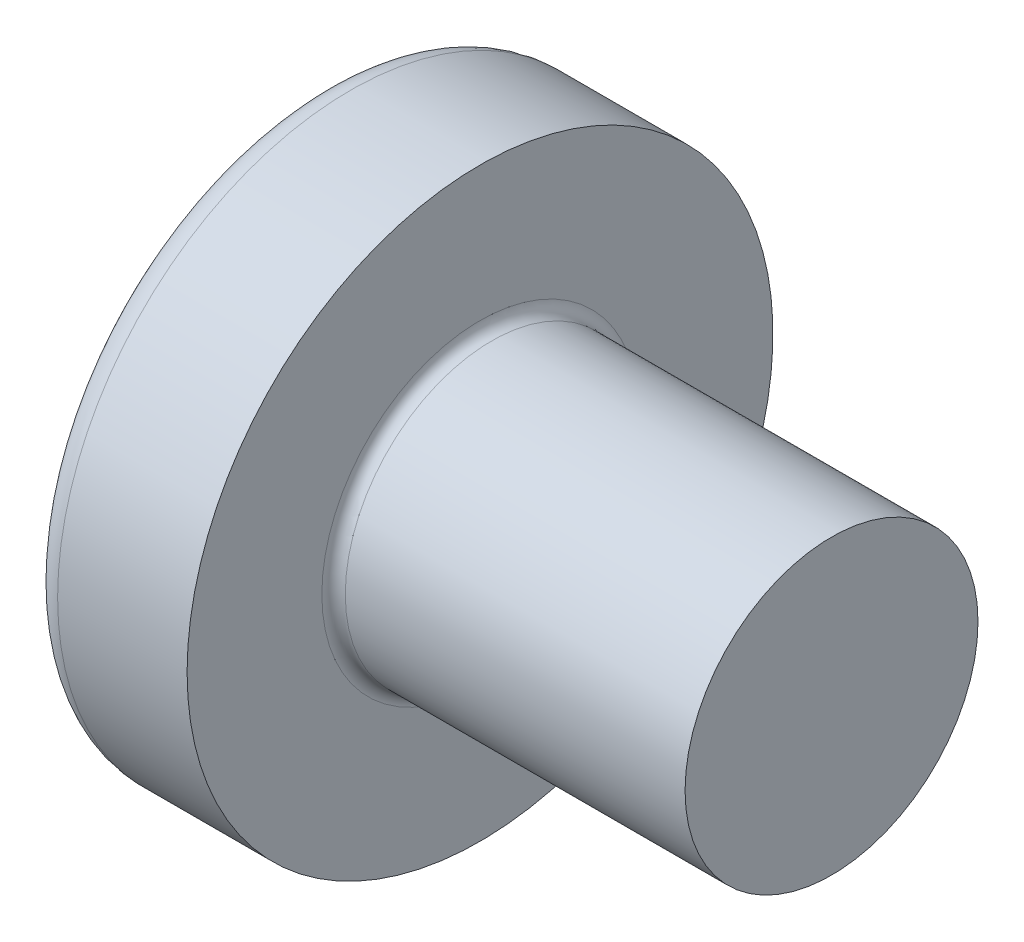
SolidWorks part; units mm, degrees
ref_plane "Plane1" through (0, 0, 0) normal (0, 0, 1) x (1, 0, 0)
ref_plane "Plane2" through (0, 0, 0) normal (0, 1, 0) x (1, 0, 0)
ref_plane "Plane3" through (0, 0, 0) normal (1, 0, 0) x (0, 0, -1)
sketch "BodySke" plane through (0, 0, 0) normal (0, 0, 1) x (1, 0, 0)
  line L0 (2.1, 1.25) -> (2.1, 2.5)
  line L1 (2.325, 6.35) -> (2.325, -3.175) construction
  line L2 (-25.4, 0) -> (127, 0) construction
  line L3 (5.1, 0) -> (0, 0)
  line L4 (2.1, 1.25) -> (5.1, 1.25)
  line L5 (5.1, 1.25) -> (5.1, 0)
  line L6 (0.995, 2.5) -> (2.1, 2.5)
  line L8 (2.1, 6.35) -> (2.1, -3.175) construction
  arc A0 (0.8032, 2.4043) -> (0, 0) centre (4, 0) ccw
  arc A2 (0.8032, 2.4043) -> (0.995, 2.5) centre (0.995, 2.26) cw
  dimension "Head_crown_rad" = 4
  dimension "Head_fillet_rad" = 0.24
  dimension "Length" = 3
  dimension "Head_ht" = 2.1
  dimension "Head_dia" = 5
  dimension "Advance" = 0.45
  dimension "Thread_nom" = 3
  dimension "Diameter" = 2.5
revolve "Base-Revolve" add sketch "BodySke"
cosmetic thread "ThreadCosmetic" [suppressed]
fillet "Fillet1" radius 0.1 1 edges at (2.1, 0, 1.25)
sketch "Sketch3" plane through (0, 0, 0) normal (1, 0, 0) x (0, 0, -1)
  line L0 (0.37, -1.3) -> (-0.37, -1.3)
  line L1 (0.37, -1.3) -> (0.37, 1.3)
  line L2 (-0.37, 1.3) -> (0.37, 1.3)
  line L3 (-0.37, 1.3) -> (-0.37, -1.3)
  dimension "Cross_dia" = 2.6
  dimension "D1" = 1.3
  dimension "Cross_width" = 0.74
  dimension "D2" = 0.37
ref_plane "Plane4" through (1.5, 0, 0) normal (1, 0, 0) x (0, 0, -1)
sketch "Sketch4" plane through (1.5, 0, 0) normal (1, 0, 0) x (0, 0, -1)
  line L0 (0.37, -0.5521) -> (-0.37, -0.5521)
  line L1 (0.37, -0.5521) -> (0.37, 0.5521)
  line L2 (-0.37, 0.5521) -> (0.37, 0.5521)
  line L3 (-0.37, 0.5521) -> (-0.37, -0.5521)
  dimension "D1" = 0.74
  dimension "D2" = 1.1043
  dimension "D3" = 0.37
  dimension "D4" = 0.5521
loft "Recess" cut profiles "Sketch3", "Sketch4"
pattern_circular "RecPat" count 2 every 90 about axis through (0, 0, 0) along (1, 0, 0) of "Recess"
sketch "RecCorSke" plane through (0, 0, 0) normal (0, 0, 1) x (1, 0, 0)
  line L0 (-3.175, 0) -> (15.875, 0) construction
  line L1 (-25.4, 0) -> (127, 0) construction
  line L2 (0, 0) -> (0, 0.6609)
  line L3 (0, 0.6609) -> (1.5, 0.556)
  line L4 (1.5, 0.556) -> (1.6807, 0)
  line L5 (1.6807, 0) -> (0, 0)
  dimension "Diameter" = 1.112
  dimension "Depth" = 1.5
  dimension "Draft_angle" = 4
  dimension "Bottom_angle" = 18
revolve "RecessCore" cut sketch "RecCorSke" angle 360 about L0
sketch "ThdSchSke" plane through (0, 0, 0) normal (0, 0, 1) x (1, 0, 0)
  line L0 (3, -0.9965) -> (2.8225, -1.25)
  line L1 (3, -0.9965) -> (3.1775, -1.25)
  line L2 (3.1775, -1.25) -> (3.1775, -1.5625)
  line L3 (-3.175, 0) -> (5.1513, 0) construction
  line L5 (3.1775, -1.5625) -> (2.8225, -1.5625)
  line L6 (2.8225, -1.5625) -> (2.8225, -1.25)
  dimension "Diameter" = 2.5
  dimension "SideAngle" = 55
  dimension "VeeAngle" = 70
  dimension "Thread_minor" = 1.993
  dimension "Overcut" = 3.125
  dimension "Start" = 3
revolve "ThreadSchematic" [suppressed] cut sketch "ThdSchSke" angle 360 about L3
pattern_linear "ThdSchPat" [suppressed]
equation "\"D1@Sketch3\" = \"Cross_dia@Sketch3\" / 2"
equation "\"D2@Sketch3\" = \"Cross_width@Sketch3\" / 2"
equation "\"Depth@RecCorSke\" = \"Cross_depth@Plane4\""
equation "\"D1@Sketch4\" = \"Cross_width@Sketch3\""
equation "\"D2@Sketch4\" = \"Cross_dia@Sketch3\" - 2.0 * \"Cross_depth@Plane4\" * tan(26.5  * 0.017453292)"
equation "\"D3@Sketch4\" = \"D1@Sketch4\" / 2"
equation "\"D4@Sketch4\" = \"D2@Sketch4\" / 2"
equation "\"Thread_length@ThreadCosmetic\" = ((sgn( (\"Length@BodySke\" - \"Advance@BodySke\" * 2.0 ) - \"Thread_nom@BodySke\" )-1)*( (\"Length@BodySke\" - \"Advance@BodySke\" * 2.0 ) - \"Thread_nom@BodySke\" ))/-2+ \"Thread_nom@BodySke\""
equation "\"Thread_minor@ThdSchSke\" = \"Thread_minor@ThreadCosmetic\""
equation "\"Diameter@ThdSchSke\" = \"Diameter@BodySke\""
equation "\"Overcut@ThdSchSke\" = \"Diameter@BodySke\" * 1.25"
equation "\"Start@ThdSchSke\" = \"Head_ht@BodySke\" + \"Length@BodySke\" - \"Thread_length@ThreadCosmetic\"  '---Non-countersunk---"
equation "\"Num_threads@ThdSchPat\" = int( \"Thread_length@ThreadCosmetic\" / \"Advance@BodySke\" + 0.999 )  + 1"
equation "\"Advance@ThdSchPat\" = \"Thread_length@ThreadCosmetic\" /  (\"Num_threads@ThdSchPat\" - 1) 'relax it"
